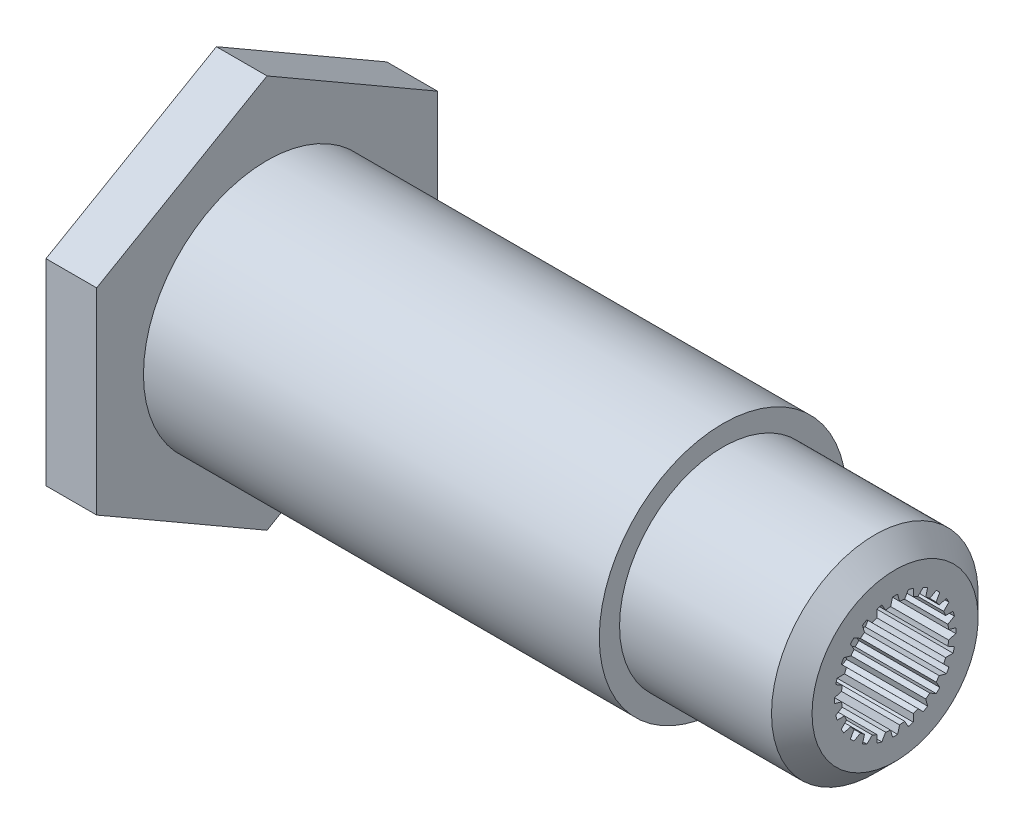
SolidWorks part; units mm, degrees
ref_plane "Спереди" through (0, 0, 0) normal (0, 0, 1) x (1, 0, 0)
ref_plane "Сверху" through (0, 0, 0) normal (0, 1, 0) x (1, 0, 0)
ref_plane "Справа" through (0, 0, 0) normal (1, 0, 0) x (0, 0, -1)
sketch "Эскиз1" plane through (0, 0, 0) normal (1, 0, 0) x (0, 0, -1)
  line L0 (0, 22.1093) -> (0, -20.4933) construction
  line L1 (23.3172, 0) -> (-29.1357, 0) construction
  line L2 (0, 10) -> (-8.6603, 5) construction
  line L3 (-8.6603, 5) -> (-8.6603, -5) construction
  line L4 (-8.6603, -5) -> (0, -10) construction
  line L5 (0, -10) -> (8.6603, -5) construction
  line L6 (8.6603, -5) -> (8.6603, 5) construction
  line L7 (8.6603, 5) -> (0, 10) construction
  line L8 (0, 9.7113) -> (-8.4103, 4.8557)
  line L9 (-8.4103, 4.8557) -> (-8.4103, -4.8557)
  line L10 (-8.4103, -4.8557) -> (0, -9.7113)
  line L11 (0, -9.7113) -> (8.4103, -4.8557)
  line L12 (8.4103, -4.8557) -> (8.4103, 4.8557)
  line L13 (8.4103, 4.8557) -> (0, 9.7113)
  circle A0 centre (0, 0) radius 10 construction
  dimension "D1" = 0.25
extrude "Бобышка-Вытянуть1" add sketch "Эскиз1" against normal blind 2.5
sketch "Эскиз3" plane through (0, 0, 0) normal (0, 0, 1) x (1, 0, 0)
  line L0 (-6.8776, 0) -> (79.0367, 0) construction
  line L1 (0, 0) -> (0, 6.1)
  line L3 (0, 6.1) -> (22.5, 6.1)
  line L4 (22.5, 6.1) -> (22.5, 5.1)
  line L5 (22.5, 5.1) -> (30, 5.1)
  line L6 (31, 4.1) -> (31, 0)
  line L7 (31, 0) -> (0, 0)
  line L9 (0, 9.7113) -> (0, 4.8557) construction
  line L10 (30, 5.1) -> (31, 4.1)
  point P10 (31, 5.1)
  dimension "D1" = 6.1
  dimension "D2" = 5.1
  dimension "D3" = 22.5
  dimension "D4" = 8.5
revolve "Повернуть1" add sketch "Эскиз3" angle 360 about L0
sketch "Эскиз4" plane through (31, 0, -31) normal (-1, 0, 0) x (0, 0, 1)
  line L3 (31, 0) -> (34.1561, 3.1561) construction
  line L9 (31, 0) -> (34.1561, -3.1561) construction
  line L15 (31, 0) -> (27.8439, -3.1561) construction
  line L21 (31, 0) -> (27.8439, 3.1561) construction
  line L27 (30.7784, 2.6407) -> (30.875, 2.9965)
  line L28 (31.2216, 2.6407) -> (31.125, 2.9965)
  line L31 (31.4694, 2.6081) -> (31.6548, 2.9268)
  line L32 (31.8975, 2.4934) -> (31.8963, 2.8621)
  line L33 (32.1284, 2.3977) -> (32.39, 2.6576)
  line L34 (32.5123, 2.1761) -> (32.6065, 2.5326)
  line L35 (32.7106, 2.024) -> (33.0305, 2.2072)
  line L36 (33.024, 1.7106) -> (33.2072, 2.0305)
  line L37 (33.1761, 1.5123) -> (33.5326, 1.6065)
  line L38 (33.3977, 1.1284) -> (33.6576, 1.39)
  line L39 (33.4934, 0.8975) -> (33.8621, 0.8963)
  line L40 (33.6081, 0.4694) -> (33.9268, 0.6548)
  line L41 (33.6407, 0.2216) -> (33.9965, 0.125)
  line L42 (33.6407, -0.2216) -> (33.9965, -0.125)
  line L43 (33.6081, -0.4694) -> (33.9268, -0.6548)
  line L44 (33.4934, -0.8975) -> (33.8621, -0.8963)
  line L45 (33.3977, -1.1284) -> (33.6576, -1.39)
  line L46 (33.1761, -1.5123) -> (33.5326, -1.6065)
  line L47 (33.024, -1.7106) -> (33.2072, -2.0305)
  line L48 (32.7106, -2.024) -> (33.0305, -2.2072)
  line L49 (32.5123, -2.1761) -> (32.6065, -2.5326)
  line L50 (32.1284, -2.3977) -> (32.39, -2.6576)
  line L51 (31.8975, -2.4934) -> (31.8963, -2.8621)
  line L52 (31.4694, -2.6081) -> (31.6548, -2.9268)
  line L53 (31.2216, -2.6407) -> (31.125, -2.9965)
  line L54 (30.7784, -2.6407) -> (30.875, -2.9965)
  line L55 (30.5306, -2.6081) -> (30.3452, -2.9268)
  line L56 (30.1025, -2.4934) -> (30.1037, -2.8621)
  line L57 (29.8716, -2.3977) -> (29.61, -2.6576)
  line L58 (29.4877, -2.1761) -> (29.3935, -2.5326)
  line L59 (29.2894, -2.024) -> (28.9695, -2.2072)
  line L60 (28.976, -1.7106) -> (28.7928, -2.0305)
  line L61 (28.8239, -1.5123) -> (28.4674, -1.6065)
  line L62 (28.6023, -1.1284) -> (28.3424, -1.39)
  line L63 (28.5066, -0.8975) -> (28.1379, -0.8963)
  line L64 (28.3919, -0.4694) -> (28.0732, -0.6548)
  line L65 (28.3593, -0.2216) -> (28.0035, -0.125)
  line L66 (28.3593, 0.2216) -> (28.0035, 0.125)
  line L67 (28.3919, 0.4694) -> (28.0732, 0.6548)
  line L68 (28.5066, 0.8975) -> (28.1379, 0.8963)
  line L69 (28.6023, 1.1284) -> (28.3424, 1.39)
  line L70 (28.8239, 1.5123) -> (28.4674, 1.6065)
  line L71 (28.976, 1.7106) -> (28.7928, 2.0305)
  line L72 (29.2894, 2.024) -> (28.9695, 2.2072)
  line L73 (29.4877, 2.1761) -> (29.3935, 2.5326)
  line L74 (29.8716, 2.3977) -> (29.61, 2.6576)
  line L75 (30.1025, 2.4934) -> (30.1037, 2.8621)
  line L76 (30.5306, 2.6081) -> (30.3452, 2.9268)
  arc A0 (31.125, 2.9965) -> (30.875, 2.9965) centre (31, 0) ccw
  arc A6 (31.4694, 2.6081) -> (31.2216, 2.6407) centre (31, 0) ccw
  arc A7 (31.8963, 2.8621) -> (31.6548, 2.9268) centre (31, 0) ccw
  arc A8 (32.1284, 2.3977) -> (31.8975, 2.4934) centre (31, 0) ccw
  arc A9 (32.6065, 2.5326) -> (32.39, 2.6576) centre (31, 0) ccw
  arc A10 (32.7106, 2.024) -> (32.5123, 2.1761) centre (31, 0) ccw
  arc A11 (33.2072, 2.0305) -> (33.0305, 2.2072) centre (31, 0) ccw
  arc A12 (33.1761, 1.5123) -> (33.024, 1.7106) centre (31, 0) ccw
  arc A13 (33.6576, 1.39) -> (33.5326, 1.6065) centre (31, 0) ccw
  arc A14 (33.4934, 0.8975) -> (33.3977, 1.1284) centre (31, 0) ccw
  arc A15 (33.9268, 0.6548) -> (33.8621, 0.8963) centre (31, 0) ccw
  arc A16 (33.6407, 0.2216) -> (33.6081, 0.4694) centre (31, 0) ccw
  arc A17 (33.9965, -0.125) -> (33.9965, 0.125) centre (31, 0) ccw
  arc A18 (33.6081, -0.4694) -> (33.6407, -0.2216) centre (31, 0) ccw
  arc A19 (33.8621, -0.8963) -> (33.9268, -0.6548) centre (31, 0) ccw
  arc A20 (33.3977, -1.1284) -> (33.4934, -0.8975) centre (31, 0) ccw
  arc A21 (33.5326, -1.6065) -> (33.6576, -1.39) centre (31, 0) ccw
  arc A22 (33.024, -1.7106) -> (33.1761, -1.5123) centre (31, 0) ccw
  arc A23 (33.0305, -2.2072) -> (33.2072, -2.0305) centre (31, 0) ccw
  arc A24 (32.5123, -2.1761) -> (32.7106, -2.024) centre (31, 0) ccw
  arc A25 (32.39, -2.6576) -> (32.6065, -2.5326) centre (31, 0) ccw
  arc A26 (31.8975, -2.4934) -> (32.1284, -2.3977) centre (31, 0) ccw
  arc A27 (31.6548, -2.9268) -> (31.8963, -2.8621) centre (31, 0) ccw
  arc A28 (31.2216, -2.6407) -> (31.4694, -2.6081) centre (31, 0) ccw
  arc A29 (30.875, -2.9965) -> (31.125, -2.9965) centre (31, 0) ccw
  arc A30 (30.5306, -2.6081) -> (30.7784, -2.6407) centre (31, 0) ccw
  arc A31 (30.1037, -2.8621) -> (30.3452, -2.9268) centre (31, 0) ccw
  arc A32 (29.8716, -2.3977) -> (30.1025, -2.4934) centre (31, 0) ccw
  arc A33 (29.3935, -2.5326) -> (29.61, -2.6576) centre (31, 0) ccw
  arc A34 (29.2894, -2.024) -> (29.4877, -2.1761) centre (31, 0) ccw
  arc A35 (28.7928, -2.0305) -> (28.9695, -2.2072) centre (31, 0) ccw
  arc A36 (28.8239, -1.5123) -> (28.976, -1.7106) centre (31, 0) ccw
  arc A37 (28.3424, -1.39) -> (28.4674, -1.6065) centre (31, 0) ccw
  arc A38 (28.5066, -0.8975) -> (28.6023, -1.1284) centre (31, 0) ccw
  arc A39 (28.0732, -0.6548) -> (28.1379, -0.8963) centre (31, 0) ccw
  arc A40 (28.3593, -0.2216) -> (28.3919, -0.4694) centre (31, 0) ccw
  arc A41 (28.0035, 0.125) -> (28.0035, -0.125) centre (31, 0) ccw
  arc A42 (28.3919, 0.4694) -> (28.3593, 0.2216) centre (31, 0) ccw
  arc A43 (28.1379, 0.8963) -> (28.0732, 0.6548) centre (31, 0) ccw
  arc A44 (28.6023, 1.1284) -> (28.5066, 0.8975) centre (31, 0) ccw
  arc A45 (28.4674, 1.6065) -> (28.3424, 1.39) centre (31, 0) ccw
  arc A46 (28.976, 1.7106) -> (28.8239, 1.5123) centre (31, 0) ccw
  arc A47 (28.9695, 2.2072) -> (28.7928, 2.0305) centre (31, 0) ccw
  arc A48 (29.4877, 2.1761) -> (29.2894, 2.024) centre (31, 0) ccw
  arc A49 (29.61, 2.6576) -> (29.3935, 2.5326) centre (31, 0) ccw
  arc A50 (30.1025, 2.4934) -> (29.8716, 2.3977) centre (31, 0) ccw
  arc A51 (30.3452, 2.9268) -> (30.1037, 2.8621) centre (31, 0) ccw
  arc A52 (30.7784, 2.6407) -> (30.5306, 2.6081) centre (31, 0) ccw
  point P31 (31, 0)
  point P39 (31, 0)
  point P151 (31, 0)
extrude "Вырез-Вытянуть1" cut sketch "Эскиз4" along normal blind 4
